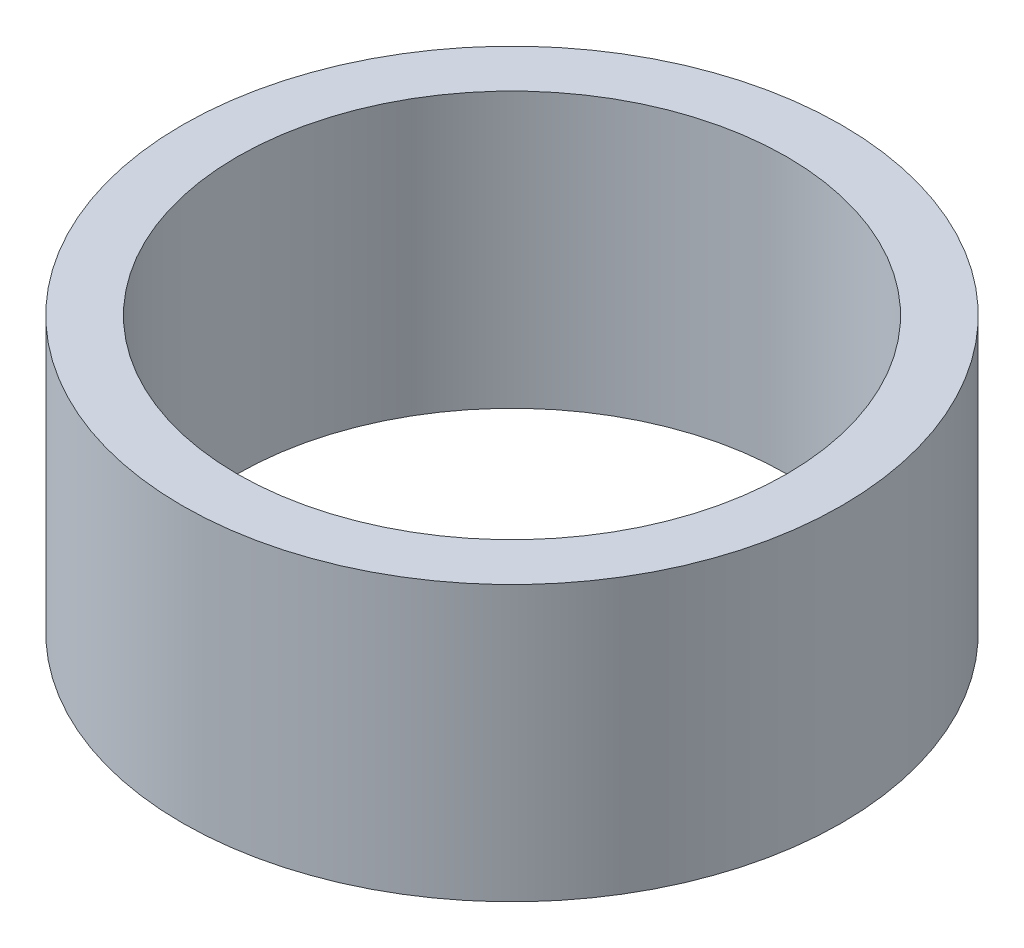
SolidWorks part; units mm, degrees
ref_plane "前视基准面" through (0, 0, 0) normal (0, 0, 1) x (1, 0, 0)
ref_plane "上视基准面" through (0, 0, 0) normal (0, 1, 0) x (1, 0, 0)
ref_plane "右视基准面" through (0, 0, 0) normal (1, 0, 0) x (0, 0, -1)
sketch "草图1" plane through (0, 0, 0) normal (0, 1, 0) x (1, 0, 0)
  circle A0 centre (0, 0) radius 5
  circle A1 centre (0, 0) radius 6
  dimension "D1" = 10
  dimension "D2" = 12
extrude "凸台-拉伸1" add sketch "草图1" along normal blind 5 contours A0 | A1
